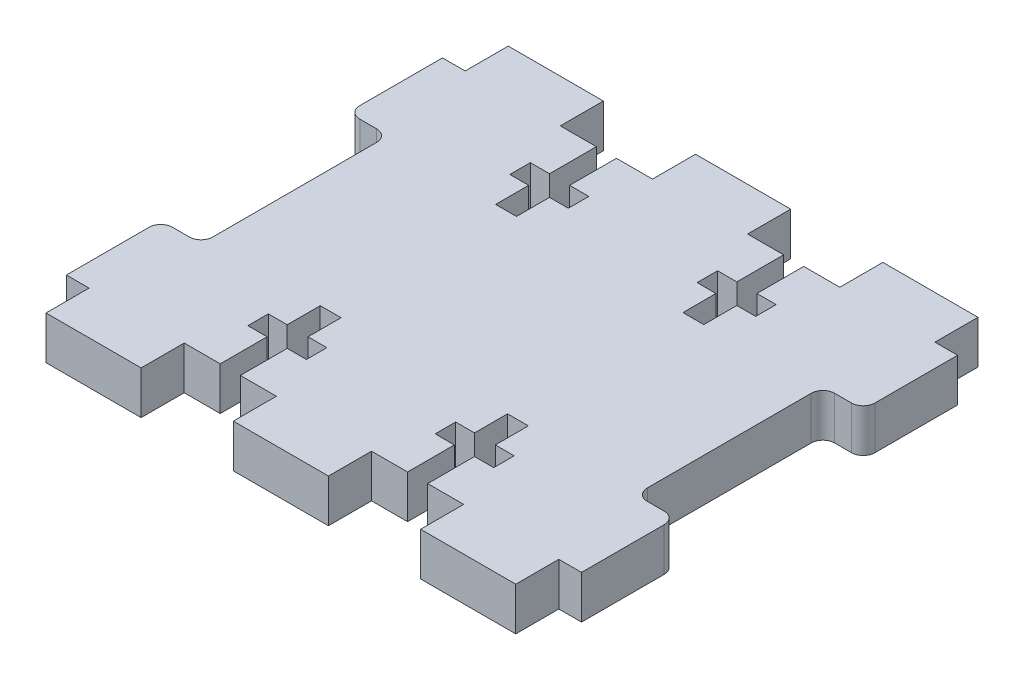
SolidWorks part; units mm, degrees
ref_plane "Front Plane" through (0, 0, 0) normal (0, 0, 1) x (1, 0, 0)
ref_plane "Top Plane" through (0, 0, 0) normal (0, 1, 0) x (1, 0, 0)
ref_plane "Right Plane" through (0, 0, 0) normal (1, 0, 0) x (0, 0, -1)
sketch "Sketch1" plane through (0, 0, 0) normal (0, 1, 0) x (1, 0, 0)
  line L0 (-6.45, 31.342) -> (-6.45, 25.5)
  line L1 (12.7, -25.5) -> (12.7, -14.1319) construction
  line L2 (34.925, -25.5) -> (34.925, 25.5)
  line L3 (34.925, 25.5) -> (31.85, 25.5)
  line L4 (-34.925, -25.5) -> (-34.925, 25.5)
  line L5 (34.925, -25.5) -> (-34.925, 25.5) construction
  line L6 (34.925, 25.5) -> (-34.925, -25.5) construction
  line L7 (-18.95, 31.342) -> (-31.85, 31.342)
  line L8 (-18.95, 31.342) -> (-18.95, 25.5)
  line L9 (-31.85, 25.5) -> (-34.925, 25.5)
  line L10 (-31.85, 31.342) -> (-31.85, 25.5)
  line L11 (-18.95, 31.342) -> (-31.85, 25.5) construction
  line L12 (-18.95, 25.5) -> (-31.85, 31.342) construction
  line L13 (6.45, 31.342) -> (-6.45, 31.342)
  line L14 (6.45, 31.342) -> (6.45, 25.5)
  line L15 (18.95, 31.342) -> (18.95, 25.5)
  line L16 (31.85, 31.342) -> (18.95, 31.342)
  line L17 (31.85, 31.342) -> (31.85, 25.5)
  line L18 (-34.925, 0) -> (34.925, 0) construction
  line L19 (0, -25.3) -> (0, 31.342) construction
  line L20 (-12.7, 25.5) -> (-12.7, 14.1319) construction
  line L21 (-14.0647, 19.15) -> (-16.6688, 19.15)
  line L22 (-11.3353, 19.15) -> (-11.3353, 25.5)
  line L23 (-14.1139, 16.3719) -> (-16.6688, 16.3719)
  line L24 (-14.0647, 19.15) -> (-14.0647, 25.5)
  line L25 (-11.3353, 19.15) -> (-14.0647, 25.5) construction
  line L26 (-11.3353, 25.5) -> (-14.0647, 19.15) construction
  line L27 (-8.7313, 16.3719) -> (-11.2861, 16.3719)
  line L28 (-8.7313, 16.3719) -> (-8.7313, 19.15)
  line L29 (-8.7313, 19.15) -> (-11.3353, 19.15)
  line L30 (-16.6688, 16.3719) -> (-16.6688, 19.15)
  line L31 (-8.7313, 16.3719) -> (-16.6688, 19.15) construction
  line L32 (-8.7313, 19.15) -> (-16.6688, 16.3719) construction
  line L33 (-11.2861, 11.892) -> (-14.1139, 11.892)
  line L34 (-11.2861, 11.892) -> (-11.2861, 16.3719)
  line L35 (11.2861, 16.3719) -> (14.1139, 11.892) construction
  line L36 (-14.1139, 11.892) -> (-14.1139, 16.3719)
  line L37 (-11.2861, 11.892) -> (-14.1139, 16.3719) construction
  line L38 (-11.2861, 16.3719) -> (-14.1139, 11.892) construction
  line L39 (-14.0647, 25.5) -> (-18.95, 25.5)
  line L40 (11.2861, 11.892) -> (14.1139, 16.3719) construction
  line L41 (8.7312, 19.15) -> (16.6687, 16.3719) construction
  line L42 (8.7312, 16.3719) -> (16.6687, 19.15) construction
  line L43 (11.3353, 25.5) -> (14.0647, 19.15) construction
  line L44 (11.3353, 19.15) -> (14.0647, 25.5) construction
  line L45 (12.7, 25.5) -> (12.7, 14.1319) construction
  line L46 (14.1139, 11.892) -> (14.1139, 16.3719)
  line L47 (11.2861, 11.892) -> (11.2861, 16.3719)
  line L48 (11.2861, 11.892) -> (14.1139, 11.892)
  line L49 (16.6687, 16.3719) -> (16.6687, 19.15)
  line L50 (8.7312, 19.15) -> (11.3353, 19.15)
  line L51 (8.7312, 16.3719) -> (8.7312, 19.15)
  line L52 (8.7312, 16.3719) -> (11.2861, 16.3719)
  line L53 (14.0647, 19.15) -> (14.0647, 25.5)
  line L54 (14.1139, 16.3719) -> (16.6687, 16.3719)
  line L55 (11.3353, 19.15) -> (11.3353, 25.5)
  line L56 (14.0647, 19.15) -> (16.6687, 19.15)
  line L57 (-6.45, 25.5) -> (-11.3353, 25.5)
  line L58 (18.95, 25.5) -> (14.0647, 25.5)
  line L59 (11.3353, 25.5) -> (6.45, 25.5)
  line L60 (11.2861, -11.892) -> (14.1139, -16.3719) construction
  line L61 (-11.2861, -16.3719) -> (-14.1139, -11.892) construction
  line L62 (-11.2861, -11.892) -> (-14.1139, -16.3719) construction
  line L63 (11.2861, -16.3719) -> (14.1139, -11.892) construction
  line L64 (-12.7, -25.5) -> (-12.7, -14.1319) construction
  line L65 (11.2861, -11.892) -> (14.1139, -11.892)
  line L66 (11.2861, -11.892) -> (11.2861, -16.3719)
  line L67 (14.1139, -11.892) -> (14.1139, -16.3719)
  line L68 (-14.1139, -11.892) -> (-14.1139, -16.3719)
  line L69 (-11.2861, -11.892) -> (-11.2861, -16.3719)
  line L70 (-11.2861, -11.892) -> (-14.1139, -11.892)
  line L71 (11.3353, -19.15) -> (14.0647, -25.5) construction
  line L72 (11.3353, -25.5) -> (14.0647, -19.15) construction
  line L73 (8.7312, -16.3719) -> (16.6687, -19.15) construction
  line L74 (8.7312, -19.15) -> (16.6687, -16.3719) construction
  line L75 (-8.7313, -19.15) -> (-16.6688, -16.3719) construction
  line L76 (-8.7313, -16.3719) -> (-16.6688, -19.15) construction
  line L77 (-11.3353, -25.5) -> (-14.0647, -19.15) construction
  line L78 (-11.3353, -19.15) -> (-14.0647, -25.5) construction
  line L79 (-18.95, -25.5) -> (-31.85, -31.342) construction
  line L80 (-18.95, -31.342) -> (-31.85, -25.5) construction
  line L81 (11.3353, -25.5) -> (6.45, -25.5)
  line L82 (18.95, -25.5) -> (14.0647, -25.5)
  line L83 (-6.45, -25.5) -> (-11.3353, -25.5)
  line L84 (14.0647, -19.15) -> (16.6687, -19.15)
  line L85 (11.3353, -19.15) -> (11.3353, -25.5)
  line L86 (14.1139, -16.3719) -> (16.6687, -16.3719)
  line L87 (14.0647, -19.15) -> (14.0647, -25.5)
  line L88 (8.7312, -16.3719) -> (11.2861, -16.3719)
  line L89 (8.7312, -16.3719) -> (8.7312, -19.15)
  line L90 (8.7312, -19.15) -> (11.3353, -19.15)
  line L91 (16.6687, -16.3719) -> (16.6687, -19.15)
  line L92 (-14.0647, -25.5) -> (-18.95, -25.5)
  line L93 (-16.6688, -16.3719) -> (-16.6688, -19.15)
  line L94 (-8.7313, -19.15) -> (-11.3353, -19.15)
  line L95 (-8.7313, -16.3719) -> (-8.7313, -19.15)
  line L96 (-8.7313, -16.3719) -> (-11.2861, -16.3719)
  line L97 (-14.0647, -19.15) -> (-14.0647, -25.5)
  line L98 (-14.1139, -16.3719) -> (-16.6688, -16.3719)
  line L99 (-11.3353, -19.15) -> (-11.3353, -25.5)
  line L100 (-14.0647, -19.15) -> (-16.6688, -19.15)
  line L101 (31.85, -31.342) -> (31.85, -25.5)
  line L102 (31.85, -31.342) -> (18.95, -31.342)
  line L103 (18.95, -31.342) -> (18.95, -25.5)
  line L104 (6.45, -31.342) -> (6.45, -25.5)
  line L105 (6.45, -31.342) -> (-6.45, -31.342)
  line L106 (-31.85, -31.342) -> (-31.85, -25.5)
  line L107 (-18.95, -31.342) -> (-18.95, -25.5)
  line L108 (-18.95, -31.342) -> (-31.85, -31.342)
  line L109 (-6.45, -31.342) -> (-6.45, -25.5)
  line L110 (-31.85, -25.5) -> (-34.925, -25.5)
  line L111 (34.925, -25.5) -> (31.85, -25.5)
  point P0 (0, 0)
  point P6 (-25.4, 28.421)
  point P23 (-12.7, 22.325)
  point P28 (-12.7, 17.7609)
  point P33 (-12.7, 14.1319)
  point P54 (12.7, 17.7609)
  point P55 (12.7, 22.325)
  point P96 (12.7, -22.325)
  point P97 (12.7, -17.7609)
  point P98 (-12.7, -17.7609)
  point P99 (-12.7, -22.325)
  point P100 (-25.4, -28.421)
  dimension "D1" = 69.85
  dimension "D2" = 51
  dimension "D3" = 12.9
  dimension "D4" = 9.525
  dimension "D5" = 5.842
  dimension "D7" = 6.35
  dimension "D8" = 2.7781
  dimension "D9" = 7.9375
  dimension "D10" = 4.4799
  dimension "D11" = 12.7
  dimension "D6" = 3
extrude "Boss-Extrude1" add sketch "Sketch1" along normal blind 5.842
sketch "Sketch2" plane through (0, 5.842, 0) normal (0, 1, 0) x (1, 0, 0)
  line L0 (34.925, 0) -> (-34.925, 0) construction
  line L1 (34.925, -25.5) -> (34.925, 25.5) construction
  line L2 (-34.925, 25.5) -> (-34.925, -25.5) construction
  line L3 (-29.4647, -12.7) -> (-29.4647, 12.7)
  line L4 (0, 31.342) -> (0, -31.342) construction
  line L5 (6.45, 31.342) -> (-6.45, 31.342) construction
  line L6 (-6.45, -31.342) -> (6.45, -31.342) construction
  line L7 (-29.4647, -12.7) -> (-34.925, -12.7)
  line L8 (-29.4647, 12.7) -> (-34.925, 12.7)
  line L9 (-34.925, 12.7) -> (-34.925, -12.7)
  line L10 (34.925, 12.7) -> (34.925, -12.7)
  line L11 (29.4647, 12.7) -> (34.925, 12.7)
  line L12 (29.4647, -12.7) -> (34.925, -12.7)
  line L13 (29.4647, -12.7) -> (29.4647, 12.7)
  point P9 (-29.4647, 0)
  point P21 (29.4647, 0)
  dimension "D1" = 25.4
extrude "Cut-Extrude1" cut sketch "Sketch2" against normal through all
fillet "Fillet2" radius 1.5875 8 edges at (34.925, 2.921, 12.7) (29.4647, 2.921, 12.7) (34.925, 2.921, -12.7) (29.4647, 2.921, -12.7) (-29.4647, 2.921, -12.7) (-34.925, 2.921, -12.7) (-34.925, 2.921, 12.7) (-29.4647, 2.921, 12.7)
